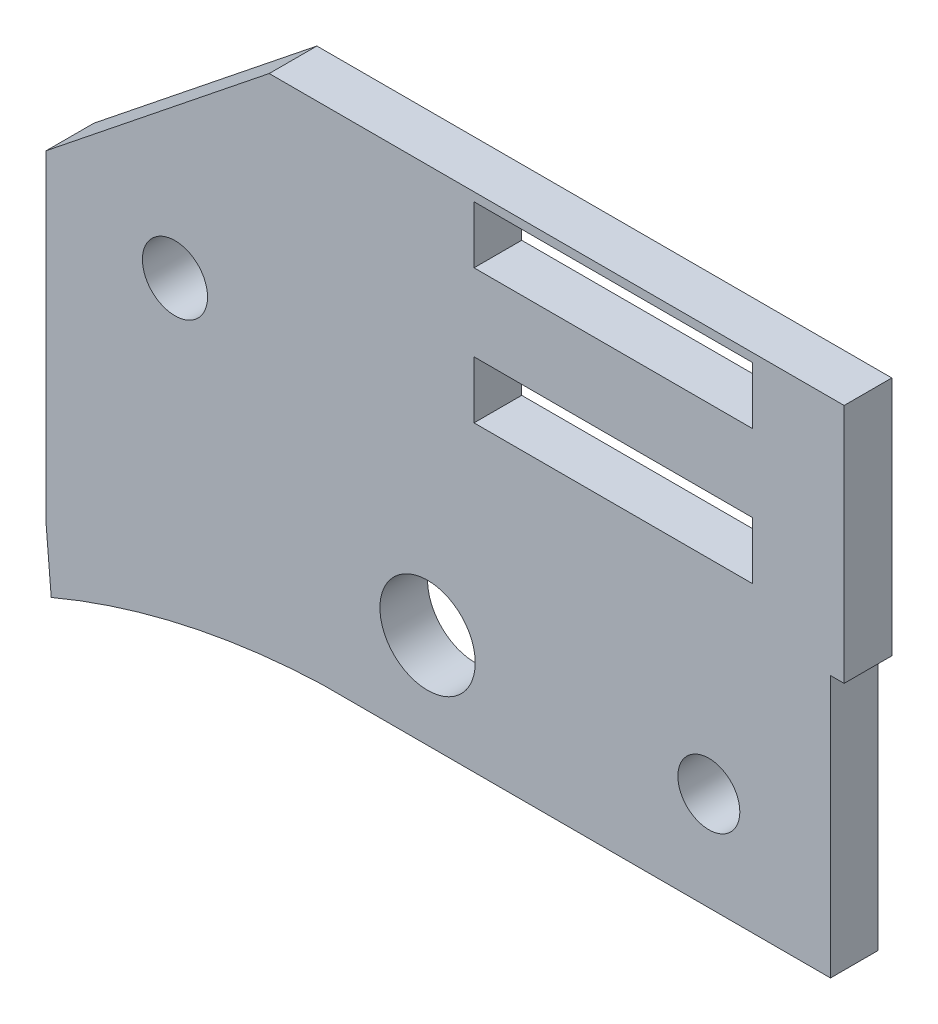
SolidWorks part; units mm, degrees
ref_plane "정면" through (0, 0, 0) normal (0, 0, 1) x (1, 0, 0)
ref_plane "윗면" through (0, 0, 0) normal (0, 1, 0) x (1, 0, 0)
ref_plane "우측면" through (0, 0, 0) normal (1, 0, 0) x (0, 0, -1)
sketch "스케치1" plane through (0, 0, 0) normal (0, 0, 1) x (1, 0, 0)
  line L0 (14.034, 31.632) -> (0, 20.4087)
  line L1 (17.3523, 0) -> (49.356, 0)
  line L2 (0, 0) -> (0, 20.4087)
  line L3 (14.034, 31.632) -> (50.2131, 31.632)
  line L4 (49.356, 0) -> (49.356, 16.4847)
  line L5 (49.356, 16.4847) -> (50.2131, 16.4847)
  line L6 (50.2131, 16.4847) -> (50.2131, 31.632)
  line L7 (0, 0) -> (0.3154, -3.781)
  line L9 (26.9241, 31.0881) -> (44.4597, 31.0881)
  line L10 (26.9241, 31.0881) -> (26.9241, 27.4881)
  line L11 (26.9241, 27.4881) -> (44.4597, 27.4881)
  line L12 (44.4597, 31.0881) -> (44.4597, 27.4881)
  line L13 (26.9241, 22.6381) -> (44.4597, 22.6381)
  line L14 (26.9241, 22.6381) -> (26.9241, 19.0381)
  line L15 (26.9241, 19.0381) -> (44.4597, 19.0381)
  line L16 (44.4597, 22.6381) -> (44.4597, 19.0381)
  circle A0 centre (24, 6) radius 3
  circle A1 centre (41.7, 6.2) radius 1.95
  arc A2 (17.3523, 0) -> (0.3154, -3.781) centre (19.0673, -48.0018) ccw
  circle A3 centre (8.1039, 17.5122) radius 2.05
  dimension "D3" = 6
  dimension "D4" = 3.9
  dimension "D9" = 4.1
  dimension "D1" = 6
  dimension "D2" = 41.7
  dimension "D5" = 3.6
  dimension "D6" = 6.2
  dimension "D7" = 128.65
  dimension "D8" = 24
  dimension "D10" = 3.6
  dimension "D11" = 4.85
extrude "보스-돌출1" add sketch "스케치1" along normal blind 3
